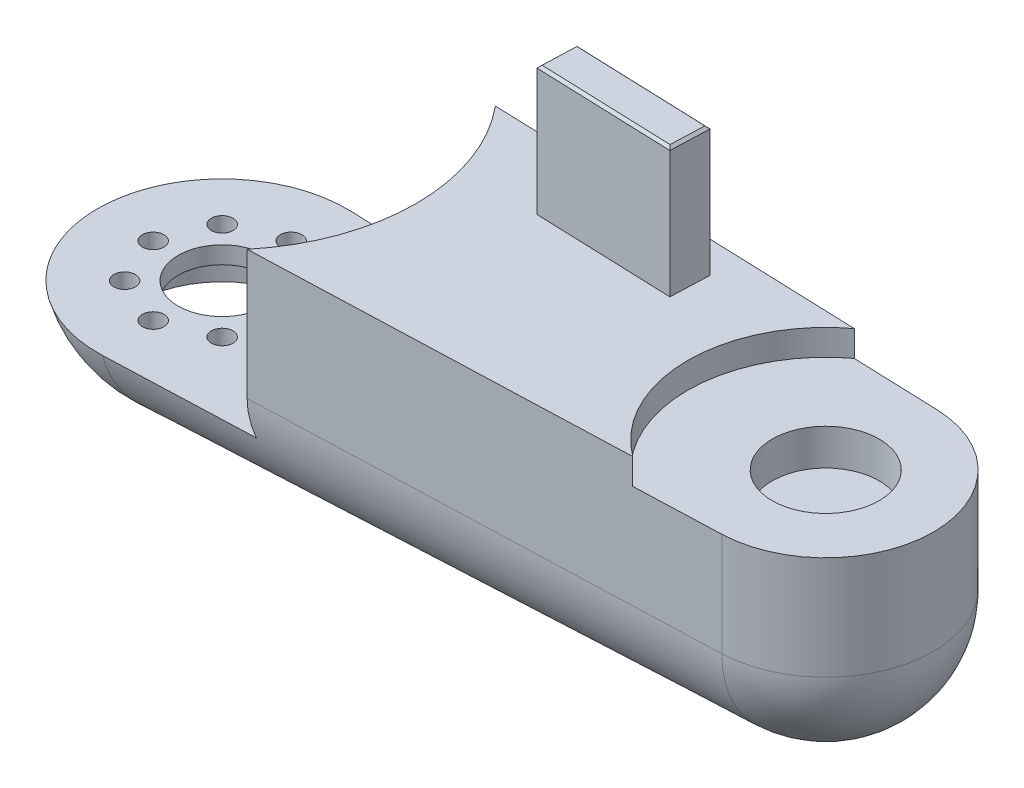
SolidWorks part; units mm, degrees
ref_plane "前视基准面" through (0, 0, 0) normal (0, 0, 1) x (1, 0, 0)
ref_plane "上视基准面" through (0, 0, 0) normal (0, 1, 0) x (1, 0, 0)
ref_plane "右视基准面" through (0, 0, 0) normal (1, 0, 0) x (0, 0, -1)
other "Configuration Table"
sketch "草图1" plane through (0, 0, 0) normal (0, 1, 0) x (1, 0, 0)
  line L2 (0.5357, -14.9904) -> (70.4464, -12.492)
  line L4 (-15, 0) -> (82.5, 0)
  arc A1 (70.4464, -12.492) -> (82.5, 0) centre (70, 0) ccw
  arc A3 (-15, 0) -> (0.5357, -14.9904) centre (0, 0) ccw
  dimension "D1" = 15
  dimension "D2" = 70
  dimension "D3" = 25
ref_axis "基准轴1" through (70, 0, 0) along (-1, 0, 0)
sketch "草图2" plane through (0, 0, 0) normal (0, 1, 0) x (1, 0, 0)
  line L0 (0.5357, 14.9904) -> (70.4464, 12.492)
  line L2 (0.5357, -14.9904) -> (70.4464, -12.492)
  line L3 (82.5, 0) -> (-15, 0)
  line L4 (0.5357, -14.9904) -> (70.4464, -12.492)
  line L5 (82.5, 0) -> (-15, 0)
  arc A2 (70.4464, -12.492) -> (82.5, 0) centre (70, 0) ccw
  arc A3 (-15, 0) -> (0.5357, -14.9904) centre (0, 0) ccw
  arc A4 (70.4464, -12.492) -> (70.4464, 12.492) centre (70, 0) ccw
  arc A5 (0.5357, 14.9904) -> (0.5357, -14.9904) centre (0, 0) ccw
  dimension "D1" = 0
extrude "凸台-拉伸1" add sketch "草图2" along normal blind 15 contours L0 A5 L5 A4 | L5 A5 L4 A4
revolve "旋转1" add sketch "草图1" angle 180 about axis through (70, 0, 0) along (-1, 0, 0)
sketch "草图3" plane through (0, 15, 0) normal (0, 1, 0) x (1, 0, 0)
  line L2 (70.4464, 12.492) -> (0.5357, 14.9904)
  line L3 (0.5357, -14.9904) -> (70.4464, -12.492)
  line L4 (17.2955, 14.3915) -> (0.5357, 14.9904)
  line L5 (0.5357, -14.9904) -> (17.2955, -14.3915)
  arc A0 (17.2955, -14.3915) -> (17.2955, 14.3915) centre (0, 0) ccw
  arc A3 (0.5357, 14.9904) -> (0.5357, -14.9904) centre (0, 0) ccw
  arc A4 (70.4464, -12.492) -> (70.4464, 12.492) centre (70, 0) ccw
  arc A5 (0.5357, 14.9904) -> (0.5357, -14.9904) centre (0, 0) ccw
  dimension "D1" = 45
  dimension "D2" = 0
extrude "切除-拉伸1" cut sketch "草图3" against normal blind 19
sketch "草图4" plane through (0, -4, 0) normal (0, 1, 0) x (1, 0, 0)
  circle A0 centre (0, 0) radius 10
  circle A1 centre (8, 0) radius 1.25
  circle A2 centre (5.6569, -5.6569) radius 1.25
  circle A3 centre (0, -8) radius 1.25
  circle A4 centre (-5.6569, -5.6569) radius 1.25
  circle A5 centre (-8, 0) radius 1.25
  circle A6 centre (-5.6569, 5.6569) radius 1.25
  circle A7 centre (0, 8) radius 1.25
  circle A8 centre (5.6569, 5.6569) radius 1.25
  circle A9 centre (0, 0) radius 5.1
  point P22 (0, 0)
  dimension "D1" = 20
  dimension "D3" = 2.5
  dimension "D5" = 10.2
  dimension "D2" = 8
  dimension "D4" = 8
ref_plane "基准面1" through (0, -6, 0) normal (0, 1, 0) x (1, 0, 0)
sketch "草图5" plane through (0, -6, 0) normal (0, 1, 0) x (1, 0, 0)
  circle A0 centre (0, 0) radius 10 construction
  circle A1 centre (0, 0) radius 10
extrude "切除-拉伸2" cut sketch "草图5" against normal through all
extrude "切除-拉伸3" cut sketch "草图4" against normal through all contours A1 | A2 | A3 | A4 | A5 | A8 | A6 | A7 | A9
sketch "草图11" plane through (0, 15, 0) normal (0, 1, 0) x (1, 0, 0)
  line L0 (70, 0) -> (93.8641, 0) construction
  line L1 (17.2955, 14.3915) -> (70.4464, 12.492) construction
  line L2 (17.2955, -14.3915) -> (70.4464, -12.492) construction
  line L3 (60.4653, 12.8487) -> (70.4464, 12.492)
  line L4 (70.4464, -12.492) -> (60.4653, -12.8487)
  arc A0 (70.4464, -12.492) -> (70.4464, 12.492) centre (70, 0) ccw construction
  arc A1 (70.4464, -12.492) -> (70.4464, 12.492) centre (70, 0) ccw
  arc A2 (60.4653, 12.8487) -> (60.4653, -12.8487) centre (70, 0) ccw
  dimension "D1" = 16
extrude "切除-拉伸5" cut sketch "草图11" against normal blind 3
sketch "草图6" plane through (0, 12, 0) normal (0, 1, 0) x (1, 0, 0)
  arc A0 (70.4464, 12.492) -> (70.4464, -12.492) centre (70, 0) ccw construction
  arc A1 (70.4464, 12.492) -> (70.4464, -12.492) centre (70, 0) ccw
  circle A2 centre (70, 0) radius 3
  circle A3 centre (70, 0) radius 6.2
  dimension "D1" = 6
  dimension "D2" = 12.4
extrude "切除-拉伸4" cut sketch "草图6" against normal blind 4.2 contours A3 A2
sketch "草图12" plane through (0, 15, 0) normal (0, 1, 0) x (1, 0, 0)
  line L1 (30.5998, 5.9109) -> (46.5896, 5.3395)
  line L3 (46.5896, 5.3395) -> (46.7503, 9.8366)
  line L8 (46.7503, 9.8366) -> (30.7605, 10.408)
  line L9 (30.7605, 10.408) -> (30.5998, 5.9109)
  line L10 (38.4535, 1.6731) -> (38.9626, 15.9198) construction
  line L11 (17.2955, 14.3915) -> (60.4653, 12.8487) construction
  line L12 (17.2955, 14.3915) -> (60.4653, 12.8487)
  dimension "D5" = 8
  dimension "D1" = 3.5
  dimension "D4" = 8
  dimension "D3" = 4.5
extrude "凸台-拉伸2" add sketch "草图12" along normal blind 15 contours L10 L1 L3 L8 | L1 L10 L8 L9
chamfer "倒角1" distance 0.3 angle 45 4 edges at (30.6802, 30, -8.1595) (38.7554, 30, -10.1223) (46.67, 30, -7.5881) (38.5947, 30, -5.6252)
sketch "草图16" plane through (0.4107, 0, -11.4927) normal (0.0357, 0, -0.9994) x (-0.9994, 0, -0.0357)
  line L0 (-41.3692, 27.5) -> (-35.3692, 27.5)
hole_wizard "孔1" positions "草图17" profile "草图18" legacy
sketch "草图17" plane through (0.4107, 0, -11.4927) normal (0.0357, 0, -0.9994) x (-0.9994, 0, -0.0357)
  point P0 (-41.3692, 27.5)
  point P3 (-35.3692, 27.5)
sketch "草图18" plane through (41.7535, 27.5, -10.0152) normal (0, 1, 0) x (-0.9994, 0, -0.0357)
  line L0 (0, 0) -> (0, 3.5)
  line L1 (0, 3.5) -> (0.85, 3.5)
  line L2 (0.85, 3.5) -> (0.85, 0)
  line L3 (0.85, 0) -> (0, 0)
  line L4 (0, 110) -> (0, -10) construction
  dimension "直径" = 1.7
  dimension "深度" = 3.5
